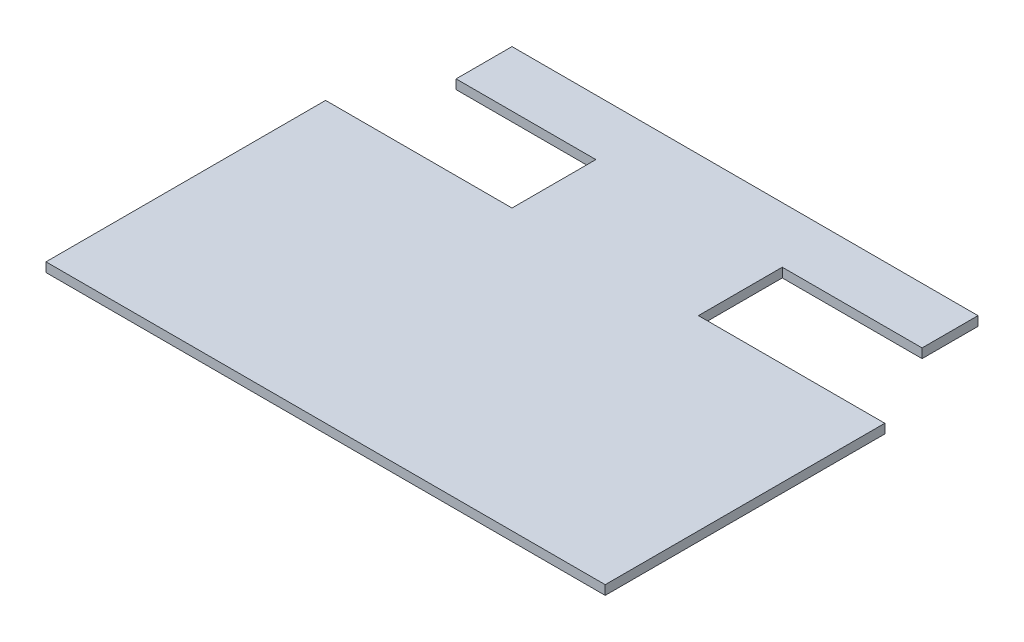
SolidWorks part; units mm, degrees
ref_plane "Front Plane" through (0, 0, 0) normal (0, 0, 1) x (1, 0, 0)
ref_plane "Top Plane" through (0, 0, 0) normal (0, 1, 0) x (1, 0, 0)
ref_plane "Right Plane" through (0, 0, 0) normal (1, 0, 0) x (0, 0, -1)
sketch "Sketch1" plane through (0, 0, 0) normal (0, 1, 0) x (1, 0, 0)
  line L0 (150, 0) -> (-150, 0)
  line L1 (0, -55) -> (0, 55) construction
  line L2 (-150, 0) -> (-150, 150)
  line L3 (-150, 150) -> (-50, 150)
  line L4 (-50, 150) -> (-50, 195)
  line L5 (-50, 195) -> (-125, 195)
  line L6 (-125, 195) -> (-125, 225)
  line L7 (-125, 225) -> (125, 225)
  line L8 (125, 195) -> (125, 225)
  line L9 (50, 195) -> (125, 195)
  line L10 (50, 150) -> (50, 195)
  line L11 (150, 150) -> (50, 150)
  line L12 (150, 0) -> (150, 150)
  line L15 (-55, 0) -> (55, 0) construction
  line L16 (-150, 75) -> (150, 75) construction
  point P11 (0, 225)
  point P16 (0, 0)
  dimension "D1" = 300
  dimension "D2" = 150
  dimension "D3" = 250
  dimension "D4" = 30
  dimension "D5" = 100
  dimension "D6" = 150
extrude "Boss-Extrude1" add sketch "Sketch1" along normal blind 5 contours L7 L8 L9 L10 L11 L12 L0 L2 L3 L4 L5 L6
equation "\"SensorWidth\"=62.6213"
equation "\"WheelMountLength\"=29.3699"
equation "\"WheelMountWidth\"=62.6213"
equation "\"SensorLength\"=8.31477"
equation "\"SensorFwdOffset\"=41.1247"
